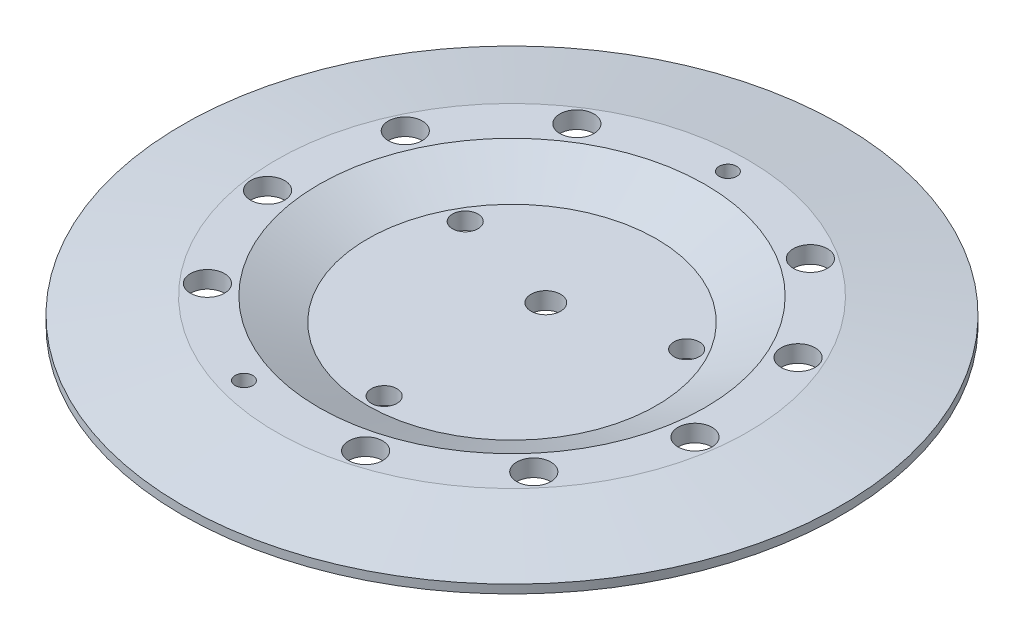
SolidWorks part; units mm, degrees
material "ABS"
ref_plane "前视基准面" through (0, 0, 0) normal (0, 0, 1) x (1, 0, 0)
ref_plane "上视基准面" through (0, 0, 0) normal (0, 1, 0) x (1, 0, 0)
ref_plane "右视基准面" through (0, 0, 0) normal (1, 0, 0) x (0, 0, -1)
sketch "草图1" plane through (0, 0, 0) normal (0, 0, 1) x (1, 0, 0)
  line L2 (25.422, 0) -> (34, 4)
  line L3 (34, 4) -> (41.5, 4)
  line L4 (41.5, 4) -> (41.5, 7) construction
  line L5 (41.5, 7) -> (34, 7)
  line L6 (34, 7) -> (25.422, 3)
  line L8 (0, 0) -> (25.422, 0)
  line L9 (0, 0) -> (0, 3)
  line L10 (0, 3) -> (25.422, 3)
  line L11 (41.5, 7) -> (58, 4.0906)
  line L12 (58, 4.0906) -> (58, 2.5906)
  line L13 (56.0098, 1.4415) -> (41.5, 4)
  line L14 (58, 2.5906) -> (56.0098, 1.4415)
  dimension "D1" = 41.5
  dimension "D2" = 34
  dimension "D3" = 3
  dimension "D4" = 25
  dimension "D5" = 4
  dimension "D6" = 58
  dimension "D7" = 170
  dimension "D8" = 60
  dimension "D9" = 1.5
revolve "旋转2" add sketch "草图1" angle 360 about L9
sketch "草图3" plane through (0, 7, 0) normal (0, 1, 0) x (1, 0, 0)
  circle A0 centre (0, 38) radius 1.55
  circle A1 centre (20.5444, 31.9676) radius 1.55
  circle A2 centre (34.566, 15.7858) radius 1.55
  circle A3 centre (37.6132, -5.408) radius 1.55
  circle A4 centre (28.7185, -24.8847) radius 1.55
  circle A5 centre (10.7058, -36.4607) radius 1.55
  circle A6 centre (-10.7058, -36.4607) radius 1.55
  circle A7 centre (-28.7185, -24.8847) radius 1.55
  circle A8 centre (-37.6132, -5.408) radius 1.55
  circle A9 centre (-34.566, 15.7858) radius 1.55
  circle A10 centre (-20.5444, 31.9676) radius 1.55
  point P32 (0, 0)
  dimension "D2" = 3.1
  dimension "D1" = 38
  dimension "D3" = 11
extrude "切除-拉伸3" cut sketch "草图3" against normal through all
sketch "草图4" plane through (0, 4, 0) normal (0, -1, 0) x (1, 0, 0)
  circle A1 centre (10.7058, 36.4607) radius 3
  circle A2 centre (28.7185, 24.8847) radius 3
  circle A3 centre (37.6132, 5.408) radius 3
  circle A4 centre (-28.7185, 24.8847) radius 3
  circle A5 centre (-34.566, -15.7858) radius 3
  circle A6 centre (-20.5444, -31.9676) radius 3
  circle A8 centre (20.5444, -31.9676) radius 3
  circle A9 centre (34.566, -15.7858) radius 3
  circle A10 centre (-37.6132, 5.408) radius 3
  dimension "D1" = 6
extrude "切除-拉伸5" cut sketch "草图4" against normal through all
sketch "草图5" plane through (0, 0, 0) normal (0, -1, 0) x (1, 0, 0)
  line L0 (0, -31.85) -> (0, 0) construction
  line L1 (19.4856, -11.25) -> (0, 22.5) construction
  line L2 (0, 22.5) -> (-19.4856, -11.25) construction
  line L3 (-19.4856, -11.25) -> (19.4856, -11.25) construction
  line L4 (0, 0) -> (-27.5829, 15.925) construction
  line L5 (0, 0) -> (27.5829, 15.925) construction
  circle A0 centre (0, 0) radius 22.5 construction
  circle A1 centre (-19.4856, -11.25) radius 2.25
  circle A2 centre (19.4856, -11.25) radius 2.25
  circle A3 centre (0, 22.5) radius 2.25
  circle A4 centre (0, 0) radius 5.95 construction
  circle A5 centre (0, -5.95) radius 2.6
  circle A6 centre (0, 0) radius 31.85 construction
  dimension "D1" = 45
  dimension "D2" = 4.5
  dimension "D3" = 11.9
  dimension "D4" = 5.2
  dimension "D5" = 63.7
  dimension "D6" = 120
  dimension "D7" = 120
extrude "切除-拉伸6" cut sketch "草图5" against normal through all
